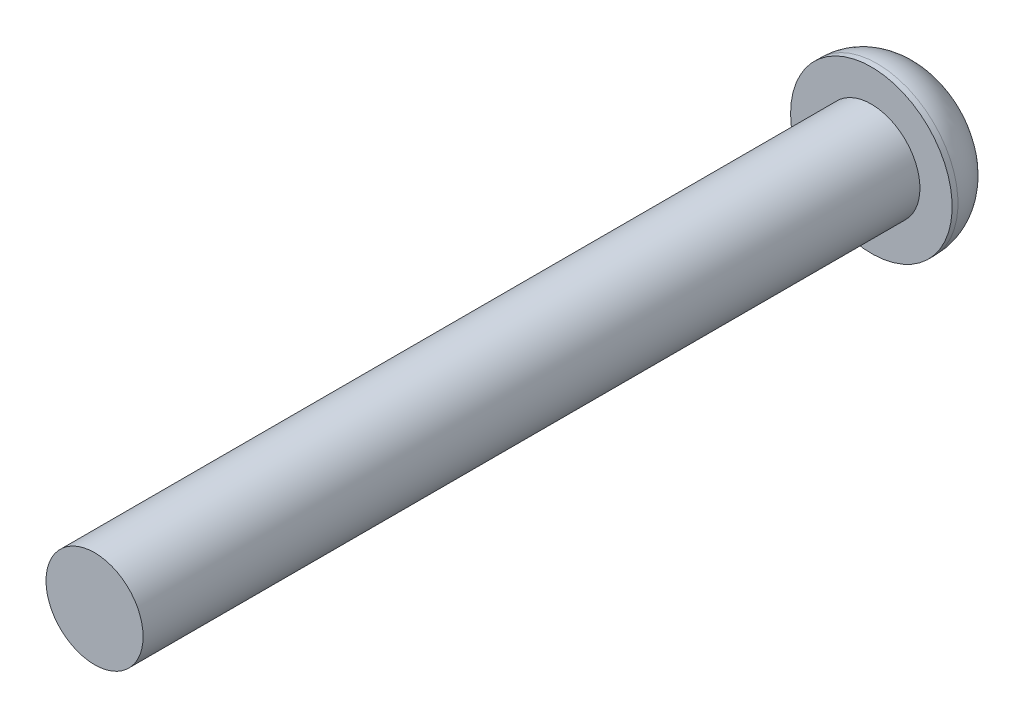
SolidWorks part; units mm, degrees
ref_plane "Front Plane" through (0, 0, 0) normal (0, 0, 1) x (1, 0, 0)
ref_plane "Top Plane" through (0, 0, 0) normal (0, 1, 0) x (1, 0, 0)
ref_plane "Right Plane" through (0, 0, 0) normal (1, 0, 0) x (0, 0, -1)
sketch "Sketch1" plane through (0, 0, 0) normal (0, 0, 1) x (1, 0, 0)
  circle A0 centre (0, 0) radius 2.5
  dimension "D1" = 5
extrude "Boss-Extrude1" add sketch "Sketch1" along normal blind 40
sketch "Sketch2" plane through (0, 0, 0) normal (0, 0, -1) x (-1, 0, 0)
  circle A0 centre (0, 0) radius 4.1596
extrude "Boss-Extrude2" add sketch "Sketch2" along normal blind 2.8
fillet "Fillet1" radius 2.5 1 edges at (-4.1596, 0, -2.8)
sketch "Sketch3" plane through (0, 0, -2.8) normal (0, 0, -1) x (-1, 0, 0)
  line L1 (1.3924, -0.6365) -> (1.2475, 0.8876)
  line L2 (1.2475, 0.8876) -> (-0.145, 1.5241)
  line L3 (-0.145, 1.5241) -> (-1.3924, 0.6365)
  line L4 (-1.3924, 0.6365) -> (-1.2475, -0.8876)
  line L5 (-1.2475, -0.8876) -> (0.145, -1.5241)
  line L6 (0.145, -1.5241) -> (1.3924, -0.6365)
  circle A0 centre (0, 0) radius 1.3259 construction
extrude "Cut-Extrude1" cut sketch "Sketch3" against normal blind 2
